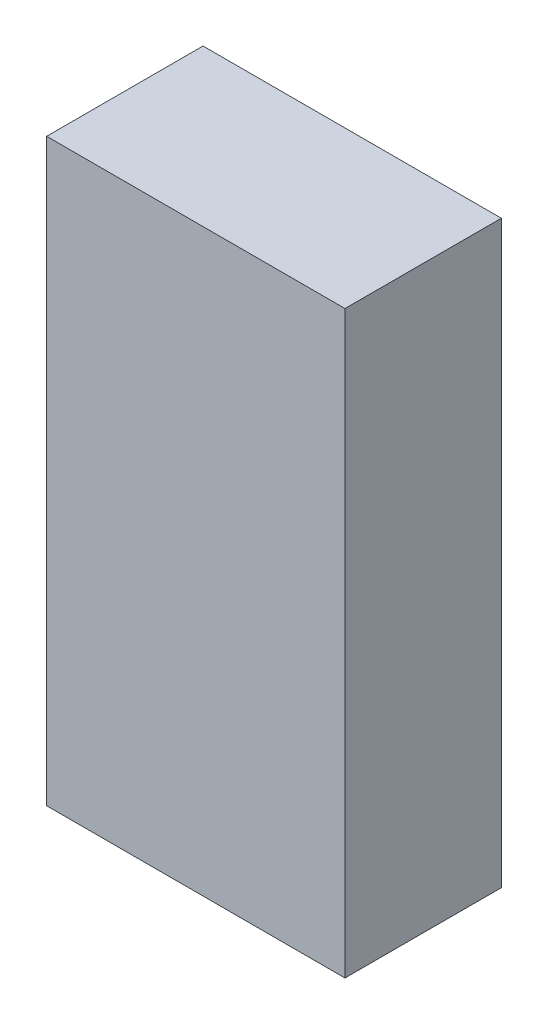
SolidWorks part; units mm, degrees
ref_plane "Front Plane" through (0, 0, 0) normal (0, 0, 1) x (1, 0, 0)
ref_plane "Top Plane" through (0, 0, 0) normal (0, 1, 0) x (1, 0, 0)
ref_plane "Right Plane" through (0, 0, 0) normal (1, 0, 0) x (0, 0, -1)
sketch "Sketch1" plane through (0, 0, 0) normal (0, 0, 1) x (1, 0, 0)
  line L1 (-62, 120.5) -> (62, 120.5)
  line L2 (-62, 120.5) -> (-62, -120.5)
  line L3 (-62, -120.5) -> (62, -120.5)
  line L4 (62, 120.5) -> (62, -120.5)
  line L5 (-62, 120.5) -> (62, -120.5) construction
  line L6 (-62, -120.5) -> (62, 120.5) construction
  point P0 (0, 0)
  dimension "D1" = 124
  dimension "D2" = 241
extrude "Boss-Extrude1" add sketch "Sketch1" along normal blind 65
